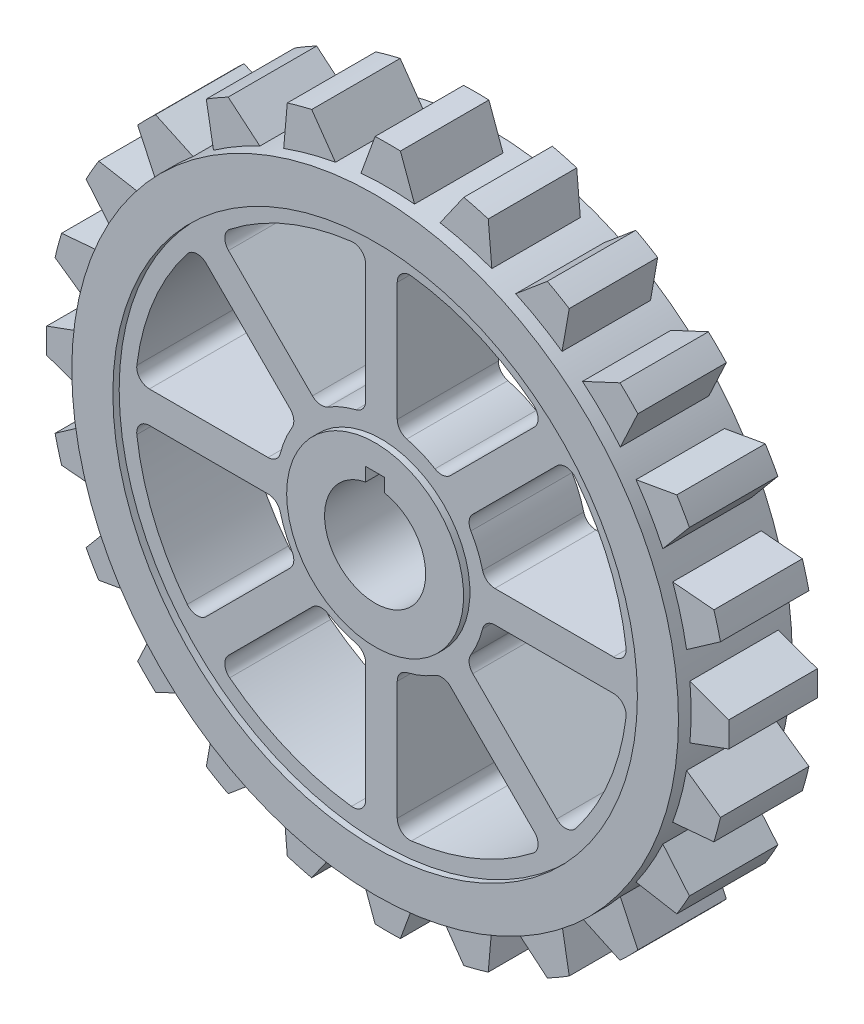
SolidWorks part; units mm, degrees
material "Cast Carbon Steel"
ref_plane "Front Plane" through (0, 0, 0) normal (0, 0, 1) x (1, 0, 0)
ref_plane "Top Plane" through (0, 0, 0) normal (0, 1, 0) x (1, 0, 0)
ref_plane "Right Plane" through (0, 0, 0) normal (1, 0, 0) x (0, 0, -1)
sketch "Sketch1" plane through (0, 0, 0) normal (0, 0, 1) x (1, 0, 0)
  line L0 (-4.2386, 47.8125) -> (-2, 53.963)
  line L1 (2, 53.963) -> (4.2386, 47.8125)
  line L2 (0, 54) -> (0, 48) construction
  line L3 (15.8985, 51.6066) -> (16.4689, 45.0863)
  line L4 (8.2806, 47.2803) -> (12.0348, 52.6418)
  line L5 (28.7135, 45.7333) -> (27.577, 39.2875)
  line L6 (20.2355, 43.5261) -> (25.2494, 47.7333)
  line L7 (39.5718, 36.7434) -> (36.8057, 30.8114)
  line L8 (30.8114, 36.8057) -> (36.7434, 39.5718)
  line L9 (47.7333, 25.2494) -> (43.5261, 20.2355)
  line L10 (39.2875, 27.577) -> (45.7333, 28.7135)
  line L11 (52.6418, 12.0348) -> (47.2803, 8.2806)
  line L12 (45.0863, 16.4689) -> (51.6066, 15.8985)
  line L13 (53.963, -2) -> (47.8125, -4.2386)
  line L14 (47.8125, 4.2386) -> (53.963, 2)
  line L15 (51.6066, -15.8985) -> (45.0863, -16.4689)
  line L16 (47.2803, -8.2806) -> (52.6418, -12.0348)
  line L17 (45.7333, -28.7135) -> (39.2875, -27.577)
  line L18 (43.5261, -20.2355) -> (47.7333, -25.2494)
  line L19 (36.7434, -39.5718) -> (30.8114, -36.8057)
  line L20 (36.8057, -30.8114) -> (39.5718, -36.7434)
  line L21 (25.2494, -47.7333) -> (20.2355, -43.5261)
  line L22 (27.577, -39.2875) -> (28.7135, -45.7333)
  line L23 (12.0348, -52.6418) -> (8.2806, -47.2803)
  line L24 (16.4689, -45.0863) -> (15.8985, -51.6066)
  line L25 (-2, -53.963) -> (-4.2386, -47.8125)
  line L26 (4.2386, -47.8125) -> (2, -53.963)
  line L27 (-15.8985, -51.6066) -> (-16.4689, -45.0863)
  line L28 (-8.2806, -47.2803) -> (-12.0348, -52.6418)
  line L29 (-28.7135, -45.7333) -> (-27.577, -39.2875)
  line L30 (-20.2355, -43.5261) -> (-25.2494, -47.7333)
  line L31 (-39.5718, -36.7434) -> (-36.8057, -30.8114)
  line L32 (-30.8114, -36.8057) -> (-36.7434, -39.5718)
  line L33 (-47.7333, -25.2494) -> (-43.5261, -20.2355)
  line L34 (-39.2875, -27.577) -> (-45.7333, -28.7135)
  line L35 (-52.6418, -12.0348) -> (-47.2803, -8.2806)
  line L36 (-45.0863, -16.4689) -> (-51.6066, -15.8985)
  line L37 (-53.963, 2) -> (-47.8125, 4.2386)
  line L38 (-47.8125, -4.2386) -> (-53.963, -2)
  line L39 (-51.6066, 15.8985) -> (-45.0863, 16.4689)
  line L40 (-47.2803, 8.2806) -> (-52.6418, 12.0348)
  line L41 (-45.7333, 28.7135) -> (-39.2875, 27.577)
  line L42 (-43.5261, 20.2355) -> (-47.7333, 25.2494)
  line L43 (-36.7434, 39.5718) -> (-30.8114, 36.8057)
  line L44 (-36.8057, 30.8114) -> (-39.5718, 36.7434)
  line L45 (-25.2494, 47.7333) -> (-20.2355, 43.5261)
  line L46 (-27.577, 39.2875) -> (-28.7135, 45.7333)
  line L47 (-12.0348, 52.6418) -> (-8.2806, 47.2803)
  line L48 (-16.4689, 45.0863) -> (-15.8985, 51.6066)
  circle A0 centre (0, 0) radius 54 construction
  arc A1 (-2, 53.963) -> (2, 53.963) centre (0, 0) cw
  arc A2 (4.2386, 47.8125) -> (-4.2386, 47.8125) centre (0, 0) ccw
  circle A3 centre (0, 0) radius 48 construction
  arc A4 (16.4689, 45.0863) -> (8.2806, 47.2803) centre (0, 0) ccw
  arc A5 (12.0348, 52.6418) -> (15.8985, 51.6066) centre (0, 0) cw
  arc A6 (27.577, 39.2875) -> (20.2355, 43.5261) centre (0, 0) ccw
  arc A7 (25.2494, 47.7333) -> (28.7135, 45.7333) centre (0, 0) cw
  arc A8 (36.8057, 30.8114) -> (30.8114, 36.8057) centre (0, 0) ccw
  arc A9 (36.7434, 39.5718) -> (39.5718, 36.7434) centre (0, 0) cw
  arc A10 (43.5261, 20.2355) -> (39.2875, 27.577) centre (0, 0) ccw
  arc A11 (45.7333, 28.7135) -> (47.7333, 25.2494) centre (0, 0) cw
  arc A12 (47.2803, 8.2806) -> (45.0863, 16.4689) centre (0, 0) ccw
  arc A13 (51.6066, 15.8985) -> (52.6418, 12.0348) centre (0, 0) cw
  arc A14 (47.8125, -4.2386) -> (47.8125, 4.2386) centre (0, 0) ccw
  arc A15 (53.963, 2) -> (53.963, -2) centre (0, 0) cw
  arc A16 (45.0863, -16.4689) -> (47.2803, -8.2806) centre (0, 0) ccw
  arc A17 (52.6418, -12.0348) -> (51.6066, -15.8985) centre (0, 0) cw
  arc A18 (39.2875, -27.577) -> (43.5261, -20.2355) centre (0, 0) ccw
  arc A19 (47.7333, -25.2494) -> (45.7333, -28.7135) centre (0, 0) cw
  arc A20 (30.8114, -36.8057) -> (36.8057, -30.8114) centre (0, 0) ccw
  arc A21 (39.5718, -36.7434) -> (36.7434, -39.5718) centre (0, 0) cw
  arc A22 (20.2355, -43.5261) -> (27.577, -39.2875) centre (0, 0) ccw
  arc A23 (28.7135, -45.7333) -> (25.2494, -47.7333) centre (0, 0) cw
  arc A24 (8.2806, -47.2803) -> (16.4689, -45.0863) centre (0, 0) ccw
  arc A25 (15.8985, -51.6066) -> (12.0348, -52.6418) centre (0, 0) cw
  arc A26 (-4.2386, -47.8125) -> (4.2386, -47.8125) centre (0, 0) ccw
  arc A27 (2, -53.963) -> (-2, -53.963) centre (0, 0) cw
  arc A28 (-16.4689, -45.0863) -> (-8.2806, -47.2803) centre (0, 0) ccw
  arc A29 (-12.0348, -52.6418) -> (-15.8985, -51.6066) centre (0, 0) cw
  arc A30 (-27.577, -39.2875) -> (-20.2355, -43.5261) centre (0, 0) ccw
  arc A31 (-25.2494, -47.7333) -> (-28.7135, -45.7333) centre (0, 0) cw
  arc A32 (-36.8057, -30.8114) -> (-30.8114, -36.8057) centre (0, 0) ccw
  arc A33 (-36.7434, -39.5718) -> (-39.5718, -36.7434) centre (0, 0) cw
  arc A34 (-43.5261, -20.2355) -> (-39.2875, -27.577) centre (0, 0) ccw
  arc A35 (-45.7333, -28.7135) -> (-47.7333, -25.2494) centre (0, 0) cw
  arc A36 (-47.2803, -8.2806) -> (-45.0863, -16.4689) centre (0, 0) ccw
  arc A37 (-51.6066, -15.8985) -> (-52.6418, -12.0348) centre (0, 0) cw
  arc A38 (-47.8125, 4.2386) -> (-47.8125, -4.2386) centre (0, 0) ccw
  arc A39 (-53.963, -2) -> (-53.963, 2) centre (0, 0) cw
  arc A40 (-45.0863, 16.4689) -> (-47.2803, 8.2806) centre (0, 0) ccw
  arc A41 (-52.6418, 12.0348) -> (-51.6066, 15.8985) centre (0, 0) cw
  arc A42 (-39.2875, 27.577) -> (-43.5261, 20.2355) centre (0, 0) ccw
  arc A43 (-47.7333, 25.2494) -> (-45.7333, 28.7135) centre (0, 0) cw
  arc A44 (-30.8114, 36.8057) -> (-36.8057, 30.8114) centre (0, 0) ccw
  arc A45 (-39.5718, 36.7434) -> (-36.7434, 39.5718) centre (0, 0) cw
  arc A46 (-20.2355, 43.5261) -> (-27.577, 39.2875) centre (0, 0) ccw
  arc A47 (-28.7135, 45.7333) -> (-25.2494, 47.7333) centre (0, 0) cw
  arc A48 (-8.2806, 47.2803) -> (-16.4689, 45.0863) centre (0, 0) ccw
  arc A49 (-15.8985, 51.6066) -> (-12.0348, 52.6418) centre (0, 0) cw
  point P105 (0, 0)
  dimension "D2" = 108
  dimension "D1" = 40
  dimension "D3" = 4
  dimension "D4" = 6
  dimension "D5" = 24
extrude "Boss-Extrude1" add sketch "Sketch1" along normal blind 14
sketch "Sketch2" plane through (0, 0, 0) normal (0, 0, 1) x (1, 0, 0)
  line L0 (-1.5, 7.8581) -> (-1.5, 10)
  line L1 (-1.5, 10) -> (1.5, 10)
  line L2 (1.5, 10) -> (1.5, 7.8581)
  circle A0 centre (0, 0) radius 48
  circle A1 centre (0, 0) radius 41.5
  circle A2 centre (0, 0) radius 14
  circle A3 centre (0, 0) radius 8 construction
  arc A4 (-1.5, 7.8581) -> (1.5, 7.8581) centre (0, 0) ccw
  point P11 (0, 10)
  dimension "D1" = 6.5
  dimension "D2" = 16
  dimension "D3" = 28
  dimension "D4" = 3
  dimension "10" = 10
extrude "Boss-Extrude2" add sketch "Sketch2" along normal offset from surface (18 mm away) 2 from offset 2 contours A0 A1 | A2 A3
sketch "Sketch3" plane through (0, 0, 0) normal (0, 0, 1) x (1, 0, 0)
  line L0 (2.5, 17.9444) -> (2.5, 36.7253)
  line L1 (24.201, 27.7365) -> (10.9208, 14.4563)
  line L2 (0, 14) -> (0, 41.5)
  line L3 (29.3449, 29.3449) -> (9.8995, 9.8995)
  line L4 (14.4563, 10.9208) -> (27.7365, 24.201)
  line L5 (36.7253, 2.5) -> (17.9444, 2.5)
  line L6 (9.8995, 9.8995) -> (29.3449, 29.3449)
  line L7 (41.5, 0) -> (14, 0)
  line L8 (17.9444, -2.5) -> (36.7253, -2.5)
  line L9 (27.7365, -24.201) -> (14.4563, -10.9208)
  line L10 (14, 0) -> (41.5, 0)
  line L11 (29.3449, -29.3449) -> (9.8995, -9.8995)
  line L12 (10.9208, -14.4563) -> (24.201, -27.7365)
  line L13 (2.5, -36.7253) -> (2.5, -17.9444)
  line L14 (9.8995, -9.8995) -> (29.3449, -29.3449)
  line L15 (0, -41.5) -> (0, -14)
  line L16 (-2.5, -17.9444) -> (-2.5, -36.7253)
  line L17 (-24.201, -27.7365) -> (-10.9208, -14.4563)
  line L18 (0, -14) -> (0, -41.5)
  line L19 (-29.3449, -29.3449) -> (-9.8995, -9.8995)
  line L20 (-14.4563, -10.9208) -> (-27.7365, -24.201)
  line L21 (-36.7253, -2.5) -> (-17.9444, -2.5)
  line L22 (-9.8995, -9.8995) -> (-29.3449, -29.3449)
  line L23 (-41.5, 0) -> (-14, 0)
  line L24 (-17.9444, 2.5) -> (-36.7253, 2.5)
  line L25 (-27.7365, 24.201) -> (-14.4563, 10.9208)
  line L26 (-14, 0) -> (-41.5, 0)
  line L27 (-29.3449, 29.3449) -> (-9.8995, 9.8995)
  line L28 (-10.9208, 14.4563) -> (-24.201, 27.7365)
  line L29 (-2.5, 36.7253) -> (-2.5, 17.9444)
  line L30 (-9.8995, 9.8995) -> (-29.3449, 29.3449)
  line L31 (0, 41.5) -> (0, 14)
  arc A0 (2.5, 36.7253) -> (4.7432, 38.7105) centre (4.5, 36.7253) cw
  arc A1 (4.7432, 38.7105) -> (24.0185, 30.7264) centre (0, 0) cw
  arc A2 (24.0185, 30.7264) -> (24.201, 27.7365) centre (22.7868, 29.1507) cw
  arc A3 (10.9208, 14.4563) -> (8.4789, 14.1548) centre (9.5066, 15.8706) cw
  arc A4 (8.4789, 14.1548) -> (4.0135, 16.0044) centre (0, 0) ccw
  arc A5 (4.0135, 16.0044) -> (2.5, 17.9444) centre (4.5, 17.9444) cw
  circle A6 centre (0, 0) radius 41.5 construction
  circle A7 centre (0, 0) radius 14 construction
  arc A8 (0, 41.5) -> (29.3449, 29.3449) centre (0, 0) cw
  arc A9 (9.8995, 9.8995) -> (0, 14) centre (0, 0) ccw
  arc A10 (14.1548, 8.4789) -> (14.4563, 10.9208) centre (15.8706, 9.5066) cw
  arc A11 (27.7365, 24.201) -> (30.7264, 24.0185) centre (29.1507, 22.7868) cw
  arc A12 (30.7264, 24.0185) -> (38.7105, 4.7432) centre (0, 0) cw
  arc A13 (38.7105, 4.7432) -> (36.7253, 2.5) centre (36.7253, 4.5) cw
  arc A14 (17.9444, 2.5) -> (16.0044, 4.0135) centre (17.9444, 4.5) cw
  arc A15 (16.0044, 4.0135) -> (14.1548, 8.4789) centre (0, 0) ccw
  arc A16 (14, 0) -> (9.8995, 9.8995) centre (0, 0) ccw
  arc A17 (29.3449, 29.3449) -> (41.5, 0) centre (0, 0) cw
  arc A18 (16.0044, -4.0135) -> (17.9444, -2.5) centre (17.9444, -4.5) cw
  arc A19 (36.7253, -2.5) -> (38.7105, -4.7432) centre (36.7253, -4.5) cw
  arc A20 (38.7105, -4.7432) -> (30.7264, -24.0185) centre (0, 0) cw
  arc A21 (30.7264, -24.0185) -> (27.7365, -24.201) centre (29.1507, -22.7868) cw
  arc A22 (14.4563, -10.9208) -> (14.1548, -8.4789) centre (15.8706, -9.5066) cw
  arc A23 (14.1548, -8.4789) -> (16.0044, -4.0135) centre (0, 0) ccw
  arc A24 (9.8995, -9.8995) -> (14, 0) centre (0, 0) ccw
  arc A25 (41.5, 0) -> (29.3449, -29.3449) centre (0, 0) cw
  arc A26 (8.4789, -14.1548) -> (10.9208, -14.4563) centre (9.5066, -15.8706) cw
  arc A27 (24.201, -27.7365) -> (24.0185, -30.7264) centre (22.7868, -29.1507) cw
  arc A28 (24.0185, -30.7264) -> (4.7432, -38.7105) centre (0, 0) cw
  arc A29 (4.7432, -38.7105) -> (2.5, -36.7253) centre (4.5, -36.7253) cw
  arc A30 (2.5, -17.9444) -> (4.0135, -16.0044) centre (4.5, -17.9444) cw
  arc A31 (4.0135, -16.0044) -> (8.4789, -14.1548) centre (0, 0) ccw
  arc A32 (0, -14) -> (9.8995, -9.8995) centre (0, 0) ccw
  arc A33 (29.3449, -29.3449) -> (0, -41.5) centre (0, 0) cw
  arc A34 (-4.0135, -16.0044) -> (-2.5, -17.9444) centre (-4.5, -17.9444) cw
  arc A35 (-2.5, -36.7253) -> (-4.7432, -38.7105) centre (-4.5, -36.7253) cw
  arc A36 (-4.7432, -38.7105) -> (-24.0185, -30.7264) centre (0, 0) cw
  arc A37 (-24.0185, -30.7264) -> (-24.201, -27.7365) centre (-22.7868, -29.1507) cw
  arc A38 (-10.9208, -14.4563) -> (-8.4789, -14.1548) centre (-9.5066, -15.8706) cw
  arc A39 (-8.4789, -14.1548) -> (-4.0135, -16.0044) centre (0, 0) ccw
  arc A40 (-9.8995, -9.8995) -> (0, -14) centre (0, 0) ccw
  arc A41 (0, -41.5) -> (-29.3449, -29.3449) centre (0, 0) cw
  arc A42 (-14.1548, -8.4789) -> (-14.4563, -10.9208) centre (-15.8706, -9.5066) cw
  arc A43 (-27.7365, -24.201) -> (-30.7264, -24.0185) centre (-29.1507, -22.7868) cw
  arc A44 (-30.7264, -24.0185) -> (-38.7105, -4.7432) centre (0, 0) cw
  arc A45 (-38.7105, -4.7432) -> (-36.7253, -2.5) centre (-36.7253, -4.5) cw
  arc A46 (-17.9444, -2.5) -> (-16.0044, -4.0135) centre (-17.9444, -4.5) cw
  arc A47 (-16.0044, -4.0135) -> (-14.1548, -8.4789) centre (0, 0) ccw
  arc A48 (-14, 0) -> (-9.8995, -9.8995) centre (0, 0) ccw
  arc A49 (-29.3449, -29.3449) -> (-41.5, 0) centre (0, 0) cw
  arc A50 (-16.0044, 4.0135) -> (-17.9444, 2.5) centre (-17.9444, 4.5) cw
  arc A51 (-36.7253, 2.5) -> (-38.7105, 4.7432) centre (-36.7253, 4.5) cw
  arc A52 (-38.7105, 4.7432) -> (-30.7264, 24.0185) centre (0, 0) cw
  arc A53 (-30.7264, 24.0185) -> (-27.7365, 24.201) centre (-29.1507, 22.7868) cw
  arc A54 (-14.4563, 10.9208) -> (-14.1548, 8.4789) centre (-15.8706, 9.5066) cw
  arc A55 (-14.1548, 8.4789) -> (-16.0044, 4.0135) centre (0, 0) ccw
  arc A56 (-9.8995, 9.8995) -> (-14, 0) centre (0, 0) ccw
  arc A57 (-41.5, 0) -> (-29.3449, 29.3449) centre (0, 0) cw
  arc A58 (-8.4789, 14.1548) -> (-10.9208, 14.4563) centre (-9.5066, 15.8706) cw
  arc A59 (-24.201, 27.7365) -> (-24.0185, 30.7264) centre (-22.7868, 29.1507) cw
  arc A60 (-24.0185, 30.7264) -> (-4.7432, 38.7105) centre (0, 0) cw
  arc A61 (-4.7432, 38.7105) -> (-2.5, 36.7253) centre (-4.5, 36.7253) cw
  arc A62 (-2.5, 17.9444) -> (-4.0135, 16.0044) centre (-4.5, 17.9444) cw
  arc A63 (-4.0135, 16.0044) -> (-8.4789, 14.1548) centre (0, 0) ccw
  arc A64 (0, 14) -> (-9.8995, 9.8995) centre (0, 0) ccw
  arc A65 (-29.3449, 29.3449) -> (0, 41.5) centre (0, 0) cw
  point P138 (0, 0)
  dimension "D6" = 2
  dimension "D1" = 2.5
  dimension "D2" = 2.5
  dimension "D3" = 2.5
  dimension "D4" = 2.5
  dimension "D5" = 45
  dimension "D7" = 8
extrude "Boss-Extrude3" add sketch "Sketch3" along normal offset from surface (16 mm away) 1 from offset 1 contours A9 L3 A8 L2 A4 A5 L0 A0 A1 A2 L1 A3 | A57 L23 A56 L27 A54 A55 A50 L24 A51 A52 A53 L25 | A65 L27 A64 L2 A62 A63 A58 L28 A59 A60 A61 L29 | A49 L19 A48 L23 A46 A47 A42 L20 A43 A44 A45 L21 | A41 L15 A40 L19 A38 A39 A34 L16 A35 A36 A37 L17 | A33 L11 A32 L15 A30 A31 A26 L12 A27 A28 A29 L13 | A25 L7 A24 L11 A22 A23 A18 L8 A19 A20 A21 L9 | A17 L3 A16 L7 A14 A15 A10 L4 A11 A12 A13 L5
equation "\"A\"= 108"
equation "\"D2@Sketch1\"=\"A\""
equation "\"B\"= 24"
equation "\"D5@Sketch1\"=\"B\""
equation "\"D1@Boss-Extrude1\"=14"
equation "\"C\"= 2.5"
equation "\"D1@Sketch3\"=\"C\""
equation "\"D3@Sketch3\"=\"C\""
equation "\"D2@Sketch3\"=\"C\""
equation "\"D4@Sketch3\"=\"C\""
